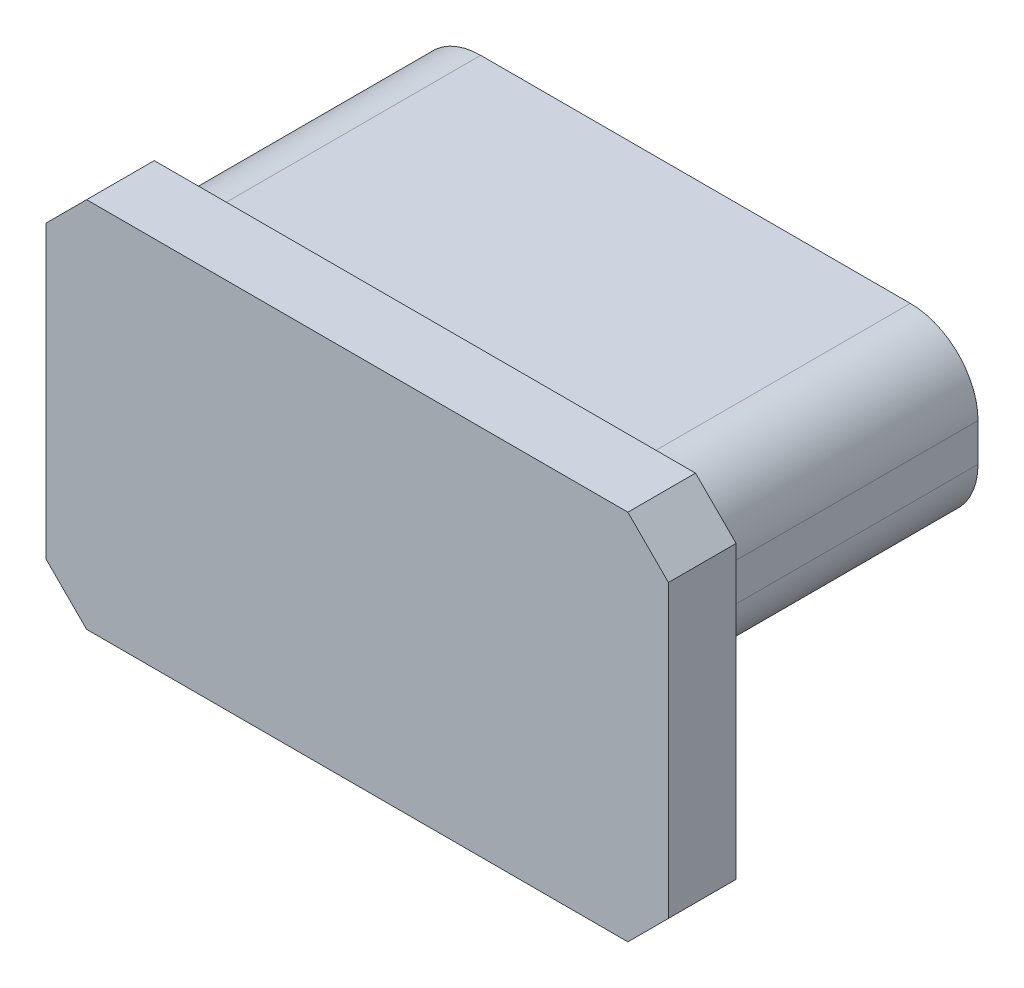
SolidWorks part; units mm, degrees
ref_plane "Front Plane" through (0, 0, 0) normal (0, 0, 1) x (1, 0, 0)
ref_plane "Top Plane" through (0, 0, 0) normal (0, 1, 0) x (1, 0, 0)
ref_plane "Right Plane" through (0, 0, 0) normal (1, 0, 0) x (0, 0, -1)
sketch "Sketch1" plane through (0, 0, 0) normal (0, 0, 1) x (1, 0, 0)
  line L0 (-1.3, -2.86) -> (-7.65, -2.86) construction
  line L1 (-0.3, -1.86) -> (-0.3, -1.3) construction
  line L2 (-8.65, -1.3) -> (-8.65, -1.86) construction
  line L3 (-7.65, -0.3) -> (-4.18, -0.3) construction
  line L4 (-4.17, -0.3) -> (-1.3, -0.3) construction
  line L5 (-4.17, -0.3) -> (-1.3, -0.3)
  line L6 (-7.65, -0.3) -> (-4.17, -0.3)
  line L7 (-8.65, -1.3) -> (-8.65, -1.86)
  line L8 (-0.3, -1.86) -> (-0.3, -1.3)
  line L9 (-1.3, -2.86) -> (-7.65, -2.86)
  arc A0 (-1.3, -2.86) -> (-0.3, -1.86) centre (-1.3, -1.86) ccw construction
  arc A1 (-0.3, -1.3) -> (-1.3, -0.3) centre (-1.3, -1.3) ccw construction
  arc A2 (-8.65, -1.86) -> (-7.65, -2.86) centre (-7.65, -1.86) ccw construction
  arc A3 (-7.65, -0.3) -> (-8.65, -1.3) centre (-7.65, -1.3) ccw construction
  arc A4 (-7.65, -0.3) -> (-8.65, -1.3) centre (-7.65, -1.3) ccw
  arc A5 (-8.65, -1.86) -> (-7.65, -2.86) centre (-7.65, -1.86) ccw
  arc A6 (-0.3, -1.3) -> (-1.3, -0.3) centre (-1.3, -1.3) ccw
  arc A7 (-1.3, -2.86) -> (-0.3, -1.86) centre (-1.3, -1.86) ccw
  point P4 (-4.1672, -0.3)
extrude "Boss-Extrude1" add sketch "Sketch1" along normal blind 5
sketch "Sketch2" plane through (0, 0, 5) normal (0, 0, 1) x (1, 0, 0)
  line L0 (-7.65, -2.86) -> (-1.3, -2.86) construction
  line L1 (0.125, -5.56) -> (-9.075, -5.56)
  line L2 (0.125, -5.56) -> (0.125, -0.06)
  line L3 (0.125, -0.06) -> (-9.075, -0.06)
  line L4 (-9.075, -5.56) -> (-9.075, -0.06)
  line L5 (-0.3, -1.58) -> (-8.65, -1.58) construction
  line L6 (-0.3, -1.86) -> (-0.3, -1.3) construction
  line L7 (-8.65, -1.3) -> (-8.65, -1.86) construction
  line L8 (-4.475, -1.58) -> (-4.475, -5.56) construction
  dimension "D1" = 5.5
  dimension "D2" = 9.2
  dimension "D3" = 2.7
extrude "Boss-Extrude2" add sketch "Sketch2" against normal blind 1
chamfer "Chamfer1" distance 0.6 angle 45 4 edges at (-9.075, -5.56, 4.5) (-9.075, -0.06, 4.5) (0.125, -5.56, 4.5) (0.125, -0.06, 4.5)
